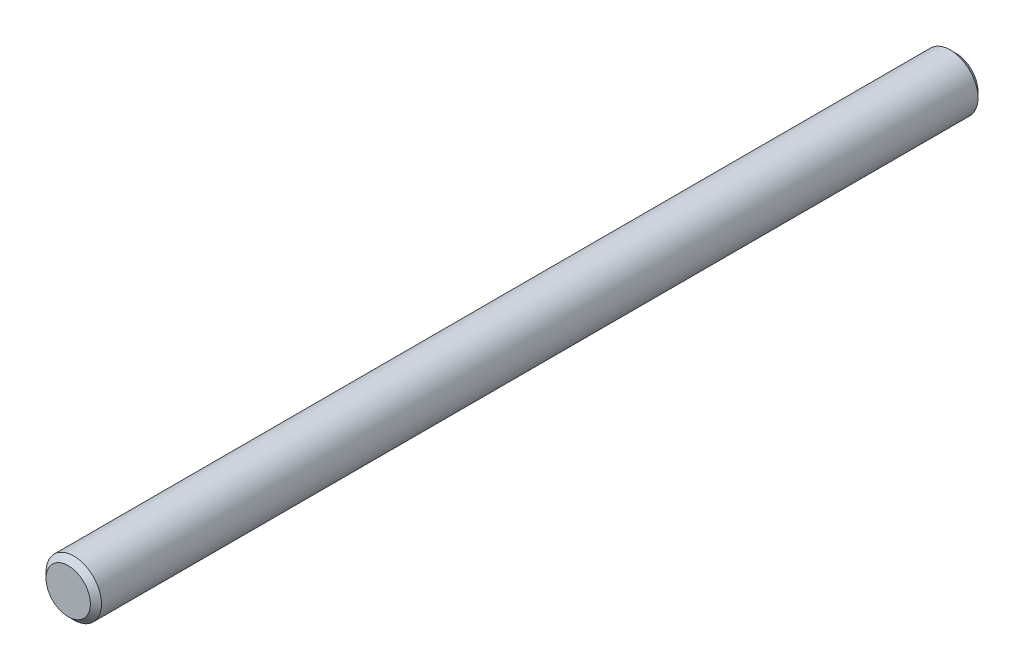
SolidWorks part; units mm, degrees
ref_plane "Front" through (0, 0, 0) normal (0, 0, 1) x (1, 0, 0)
ref_plane "Top" through (0, 0, 0) normal (0, 1, 0) x (1, 0, 0)
ref_plane "Right" through (0, 0, 0) normal (1, 0, 0) x (0, 0, -1)
sketch "Sketch1" plane through (0, 0, 0) normal (0, 0, 1) x (1, 0, 0)
  circle A0 centre (0, 0) radius 3.175
  dimension "dia" = 6.35
extrude "Extrude1" add sketch "Sketch1" along normal mid plane 101.6
sketch "Sketch2" plane through (0, 0, 0) normal (1, 0, 0) x (0, 0, -1)
  point P0 (-50.8, 3.175)
  point P1 (50.8, 3.175)
chamfer "Chamfer1" distance 0.635 angle 45 2 edges at (3.175, 0, -50.8) (3.175, 0, 50.8)
equation "\"D1@Chamfer1\" = \"dia@Sketch1\" * .1"
